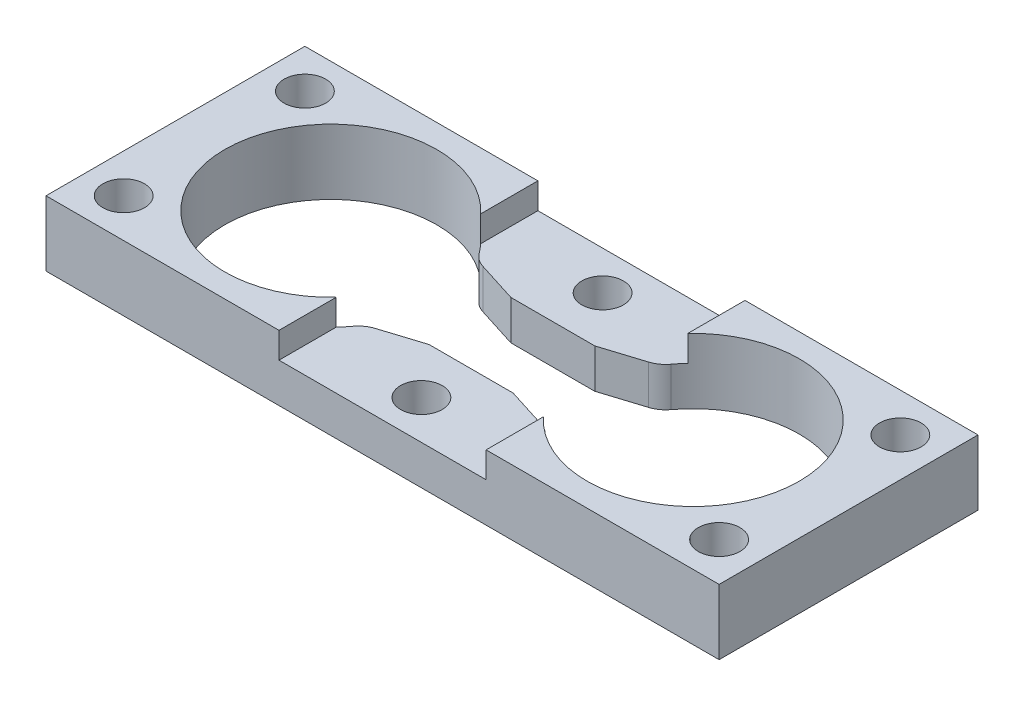
SolidWorks part; units mm, degrees
material "Delrin 2700 NC010, Low Viscosity Acetal Copolymer (SS)"
ref_plane "Front Plane" through (0, 0, 0) normal (0, 0, 1) x (1, 0, 0)
ref_plane "Top Plane" through (0, 0, 0) normal (0, 1, 0) x (1, 0, 0)
ref_plane "Right Plane" through (0, 0, 0) normal (1, 0, 0) x (0, 0, -1)
sketch "Sketch1" plane through (0, 0, 0) normal (0, 1, 0) x (1, 0, 0)
  line L1 (-41.275, -15.875) -> (41.275, -15.875)
  line L2 (-41.275, -15.875) -> (-41.275, 15.875)
  line L3 (-41.275, 15.875) -> (41.275, 15.875)
  line L4 (41.275, -15.875) -> (41.275, 15.875)
  line L5 (-41.275, -15.875) -> (41.275, 15.875) construction
  line L6 (-41.275, 15.875) -> (41.275, -15.875) construction
  point P0 (0, 0)
  dimension "D1" = 82.55
  dimension "D2" = 31.75
extrude "Plate" add sketch "Sketch1" along normal mid plane 8
hole_wizard "#10 Clearance Hole1" positions "Sketch3" profile "Sketch2" hole size "#10" standard "ANSI Inch" end condition through all
sketch "Sketch3" plane through (0, 4, 0) normal (0, 1, 0) x (1, 0, 0)
  line L12 (36.5125, -11.1125) -> (36.5125, 11.1125)
  line L13 (36.5125, 11.1125) -> (-36.5125, 11.1125)
  line L14 (-36.5125, 11.1125) -> (-36.5125, -11.1125)
  line L15 (-36.5125, -11.1125) -> (36.5125, -11.1125)
  line L16 (36.5125, -11.1125) -> (36.5125, 11.1125)
  line L17 (36.5125, 11.1125) -> (-36.5125, 11.1125)
  line L18 (-36.5125, 11.1125) -> (-36.5125, -11.1125)
  line L19 (-36.5125, -11.1125) -> (36.5125, -11.1125)
  point P0 (-36.5125, 11.1125)
  point P4 (36.5125, 11.1125)
  point P6 (36.5125, -11.1125)
  point P10 (-36.5125, -11.1125)
  point P41 (0, -11.1125)
  point P43 (0, 11.1125)
  dimension "D1" = 4.7625
sketch "Sketch2" plane through (-36.5125, 4, -11.1125) normal (1, 0, 0) x (0, 0, 1)
  line L0 (0, 0) -> (0, 8)
  line L1 (0, 8) -> (2.5527, 8)
  line L2 (2.5527, 8) -> (2.5527, 0)
  line L5 (2.5527, 0) -> (0, 0)
  line L11 (0, -6.35) -> (0, 107.95) construction
  dimension "Thru Hole Dia." = 5.1054
  dimension "Thru Hole Depth" = 8
sketch "Sketch4" plane through (0, 4, 0) normal (0, 1, 0) x (1, 0, 0)
  line L0 (-11.5479, 6.5) -> (-5.225, 4.5) construction
  line L1 (-5.225, 4.5) -> (0, 4.5) construction
  line L2 (0, 4.5) -> (0, -4.5) construction
  line L3 (0, -4.5) -> (-5.225, -4.5) construction
  line L4 (-5.225, -4.5) -> (-11.5479, -6.5) construction
  line L5 (-34.725, 0) -> (-5.225, 0) construction
  line L6 (-11.2151, 6.9275) -> (-5.1466, 5.008)
  line L7 (-5.1466, 5.008) -> (0.508, 5.008)
  line L8 (0.508, 5.008) -> (0.508, -5.008)
  line L9 (0.508, -5.008) -> (-5.1466, -5.008)
  line L10 (-5.1466, -5.008) -> (-11.2151, -6.9275)
  arc A0 (-11.5479, 6.5) -> (-11.5479, -6.5) centre (-22.225, 0) ccw construction
  arc A1 (-11.2151, 6.9275) -> (-11.2151, -6.9275) centre (-22.225, 0) ccw
  dimension "D1" = 12.5
  dimension "D3" = 13
  dimension "D5" = 29.5
  dimension "D2" = 22.225
  dimension "D4" = 9
  dimension "D6" = 0.508
extrude "Load Cell Cutout" cut sketch "Sketch4" against normal up to next
mirror "Cutout Mirror" about plane through (0, 0, 0) normal (1, 0, 0) of "Load Cell Cutout"
fillet "Fillet1" radius 3.175 4 edges at (11.2151, 0, 6.9275) (-11.2151, 0, 6.9275) (11.2151, 0, -6.9275) (-11.2151, 0, -6.9275)
sketch "Sketch5" plane through (0, 0, 15.875) normal (0, 0, 1) x (1, 0, 0)
  line L1 (-41.275, 4) -> (41.275, 4) construction
  line L2 (-12.7, 4) -> (12.7, 4)
  line L3 (-12.7, 4) -> (-12.7, 0.825)
  line L4 (-12.7, 0.825) -> (12.7, 0.825)
  line L5 (12.7, 4) -> (12.7, 0.825)
  line L6 (0, 0.825) -> (0, 4) construction
  dimension "D1" = 25.4
  dimension "D2" = 3.175
sketch "Sketch8" plane through (0, 0, 15.875) normal (0, 0, 1) x (1, 0, 0)
  line L1 (-12.7, 4) -> (12.7, 4)
  line L2 (-12.7, 4) -> (-12.7, 0.825)
  line L3 (-12.7, 0.825) -> (12.7, 0.825)
  line L4 (12.7, 4) -> (12.7, 0.825)
extrude "Cable Cutout" cut sketch "Sketch8" against normal through all
